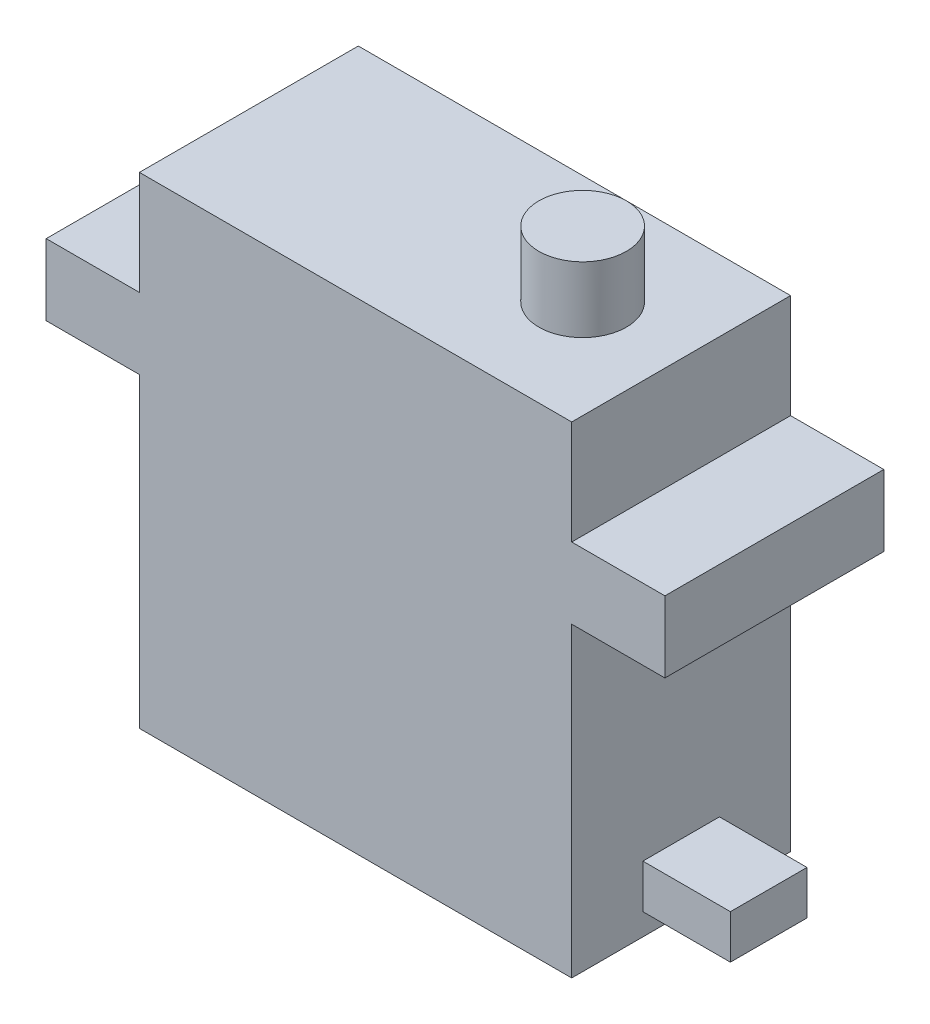
SolidWorks part; units mm, degrees
ref_plane "Front Plane" through (0, 0, 0) normal (0, 0, 1) x (1, 0, 0)
ref_plane "Top Plane" through (0, 0, 0) normal (0, 1, 0) x (1, 0, 0)
ref_plane "Right Plane" through (0, 0, 0) normal (1, 0, 0) x (0, 0, -1)
sketch "Sketch1" plane through (0, 0, 0) normal (0, 1, 0) x (1, 0, 0)
  line L1 (-43.1512, 19.0287) -> (-3.6512, 19.0287)
  line L2 (-43.1512, 19.0287) -> (-43.1512, -0.9713)
  line L3 (-43.1512, -0.9713) -> (-3.6512, -0.9713)
  line L4 (-3.6512, 19.0287) -> (-3.6512, -0.9713)
  dimension "D1" = 39.5
  dimension "D2" = 20
extrude "Boss-Extrude1" add sketch "Sketch1" along normal blind 28
sketch "Sketch2" plane through (0, 28, 0) normal (0, 1, 0) x (1, 0, 0)
  line L0 (-43.1512, 19.0287) -> (-51.6682, 19.0287)
  line L1 (-51.6682, 19.0287) -> (-51.6682, -0.9713)
  line L2 (-51.6682, -0.9713) -> (-43.1512, -0.9713)
  line L3 (-43.1512, -0.9713) -> (-3.6512, -0.9713)
  line L4 (-43.1512, -0.9713) -> (-3.6512, -0.9713) construction
  line L6 (-3.6512, 19.0287) -> (-43.1512, 19.0287) construction
  line L7 (-3.6512, 19.0287) -> (-43.1512, 19.0287)
  line L8 (-23.4012, 22.5508) -> (-23.4012, -4.3855) construction
  line L9 (4.8657, -0.9713) -> (-3.6512, -0.9713)
  line L10 (4.8657, 19.0287) -> (4.8657, -0.9713)
  line L11 (-3.6512, 19.0287) -> (4.8657, 19.0287)
  point P15 (-23.4012, -0.9713)
  point P16 (-23.4012, 19.0287)
extrude "Boss-Extrude2" add sketch "Sketch2" along normal blind 6.5 contours L3 L9 L10 L11 L7 L0 L1 L2
sketch "Sketch3" plane through (0, 34.5, 0) normal (0, 1, 0) x (1, 0, 0)
  line L0 (-23.4012, 19.0287) -> (-23.4012, -0.9713) construction
  line L1 (-51.6682, 19.0287) -> (4.8657, 19.0287) construction
  line L2 (-51.6682, -0.9713) -> (4.8657, -0.9713) construction
  line L3 (-43.1512, 19.0287) -> (-3.6512, 19.0287)
  line L4 (-3.6512, 19.0287) -> (-3.6512, -0.9713)
  line L5 (-3.6512, -0.9713) -> (-43.1512, -0.9713)
  line L7 (-43.1512, 19.0287) -> (-43.1512, -0.9713)
  dimension "D1" = 39.5
extrude "Boss-Extrude3" add sketch "Sketch3" along normal blind 9.5 contours L7 L5 L4 L3
sketch "Sketch4" plane through (0, 44, 0) normal (0, 1, 0) x (1, 0, 0)
  line L0 (-3.6512, -0.9713) -> (-12.6512, -0.9713)
  line L1 (-3.6512, -0.9713) -> (-43.1512, -0.9713) construction
  line L2 (-12.6512, -0.9713) -> (-12.6512, 19.0287)
  line L3 (-43.1512, 19.0287) -> (-3.6512, 19.0287) construction
  circle A0 centre (-12.6512, 9.0287) radius 4
  dimension "D2" = 8
  dimension "D1" = 9
extrude "Boss-Extrude4" add sketch "Sketch4" along normal blind 6 contours A0
sketch "Sketch5" plane through (-3.6512, 0, 0) normal (1, 0, 0) x (0, 0, -1)
  line L3 (5.5287, 6) -> (12.5287, 6)
  line L4 (5.5287, 6) -> (5.5287, 2)
  line L5 (5.5287, 2) -> (12.5287, 2)
  line L6 (12.5287, 6) -> (12.5287, 2)
  dimension "D2" = 4
  dimension "D3" = 7
extrude "Boss-Extrude5" add sketch "Sketch5" along normal blind 8 contours L4 L3 L6 L5
